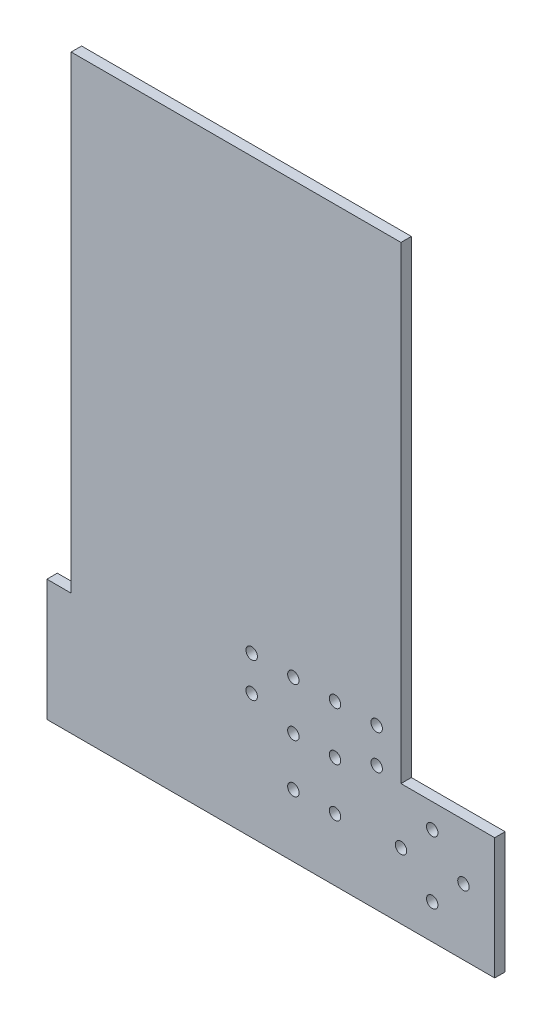
SolidWorks part; units mm, degrees
ref_plane "前视基准面" through (0, 0, 0) normal (0, 0, 1) x (1, 0, 0)
ref_plane "上视基准面" through (0, 0, 0) normal (0, 1, 0) x (1, 0, 0)
ref_plane "右视基准面" through (0, 0, 0) normal (1, 0, 0) x (0, 0, -1)
other "Configuration Table"
sketch "草图1" plane through (0, 0, 0) normal (0, 0, 1) x (1, 0, 0)
  line L0 (19, -7) -> (19, -16) construction
  line L1 (0, 0) -> (105, 0)
  line L2 (0, 0) -> (0, -35)
  line L3 (0, -35) -> (105, -35)
  line L4 (105, 0) -> (105, -35)
  line L5 (19, -25) -> (28, -16) construction
  line L6 (28, -16) -> (19, -7) construction
  line L7 (19, -7) -> (10, -16) construction
  line L8 (10, -16) -> (19, -25) construction
  circle A0 centre (19, -16) radius 6.364 construction
  dimension "D1" = 9
  dimension "D3" = 35
  dimension "D4" = 105
  dimension "D5" = 19
  dimension "D6" = 16
extrude "凸台-拉伸1" add sketch "草图1" along normal blind 3
sketch "草图3" plane through (0, 0, 3) normal (0, 0, 1) x (1, 0, 0)
  line L0 (0, 0) -> (-24, 0)
  line L1 (-24, 0) -> (-24, -35)
  line L2 (-24, -35) -> (0, -35)
  line L3 (0, -35) -> (0, 0)
  dimension "D1" = 24
extrude "凸台-拉伸2" add sketch "草图3" against normal blind 3
sketch "草图4" plane through (0, 0, 3) normal (0, 0, 1) x (1, 0, 0)
  line L0 (-17, 0) -> (-17, 135)
  line L1 (105, 0) -> (-24, 0) construction
  line L2 (-17, 135) -> (78, 135)
  line L3 (78, 135) -> (78, 0)
  line L4 (78, 0) -> (-17, 0)
  line L5 (-24, 0) -> (-24, -35) construction
  dimension "D1" = 135
  dimension "D2" = 7
  dimension "D3" = 95
extrude "凸台-拉伸3" add sketch "草图4" against normal blind 3
sketch "草图5" plane through (0, 0, 0) normal (0, 0, -1) x (-1, 0, 0)
  circle A0 centre (-87, -16) radius 12 construction
  circle A1 centre (-87, -16) radius 12 construction
  circle A2 centre (-87, -16) radius 9 construction
  circle A3 centre (-87, -7) radius 1.65
  circle A4 centre (-96, -16) radius 1.65
  circle A5 centre (-87, -25) radius 1.65
  circle A6 centre (-78, -16) radius 1.65
  dimension "D1" = 18
  dimension "D2" = 3.3
extrude "切除-拉伸1" cut sketch "草图5" against normal through all
sketch "草图6" plane through (0, 0, 3) normal (0, 0, 1) x (1, 0, 0)
  circle A1 centre (35, 1) radius 1.65
  circle A2 centre (35, 1) radius 1.65
  circle A3 centre (35, 11) radius 1.65
  circle A4 centre (35, 11) radius 1.65
  circle A5 centre (71, 1) radius 1.65
  circle A6 centre (71, 1) radius 1.65
  circle A7 centre (71, 11) radius 1.65
  circle A8 centre (71, 11) radius 1.65
  circle A9 centre (47, -17) radius 1.65
  circle A10 centre (47, -17) radius 1.65
  circle A11 centre (59, -17) radius 1.65
  circle A12 centre (59, -17) radius 1.65
  circle A13 centre (59, -3) radius 1.65
  circle A14 centre (59, -3) radius 1.65
  circle A15 centre (47, -3) radius 1.65
  circle A16 centre (47, -3) radius 1.65
  circle A17 centre (59, 11) radius 1.65
  circle A18 centre (59, 11) radius 1.65
  circle A19 centre (47, 11) radius 1.65
  circle A20 centre (47, 11) radius 1.65
  dimension "D1" = 0
  dimension "D2" = 0
  dimension "D3" = 0
  dimension "D4" = 0
  dimension "D5" = 0
  dimension "D6" = 0
  dimension "D7" = 0
  dimension "D8" = 0
  dimension "D9" = 0
  dimension "D10" = 0
extrude "切除-拉伸2" cut sketch "草图6" against normal blind 40
